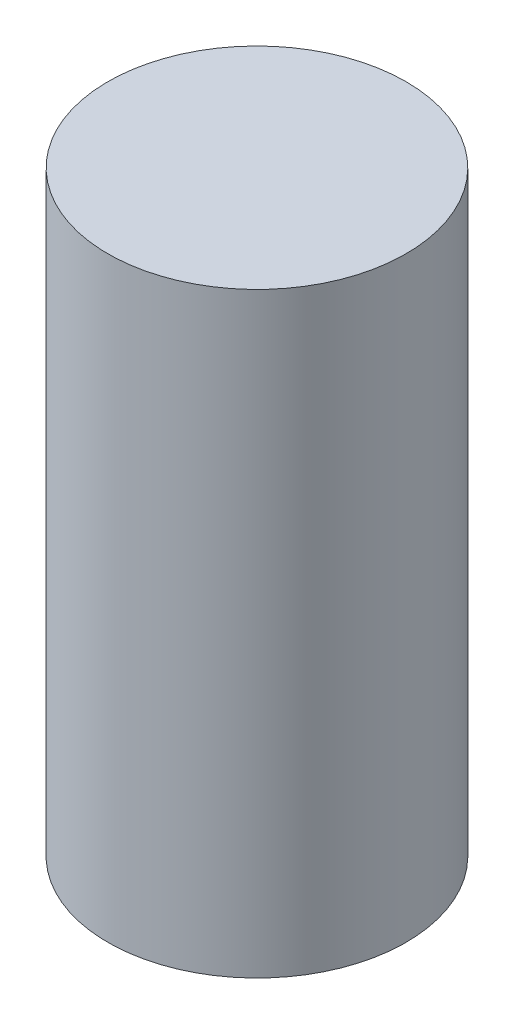
SolidWorks part; units mm, degrees
ref_plane "Front Plane" through (0, 0, 0) normal (0, 0, 1) x (1, 0, 0)
ref_plane "Top Plane" through (0, 0, 0) normal (0, 1, 0) x (1, 0, 0)
ref_plane "Right Plane" through (0, 0, 0) normal (1, 0, 0) x (0, 0, -1)
sketch "Sketch1" plane through (0, 0, 0) normal (0, 1, 0) x (1, 0, 0)
  circle A0 centre (0, 0) radius 4.7625
  dimension "D1" = 9.525
extrude "Boss-Extrude1" add sketch "Sketch1" along normal blind 19.05
